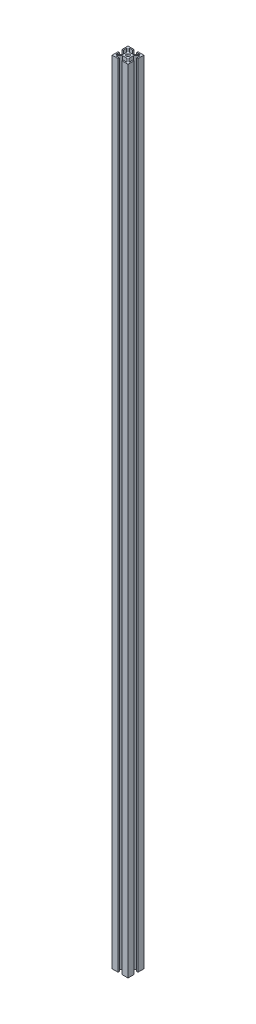
SolidWorks part; units mm, degrees
ref_plane "Front Plane" through (0, 0, 0) normal (0, 0, 1) x (1, 0, 0)
ref_plane "Top Plane" through (0, 0, 0) normal (0, 1, 0) x (1, 0, 0)
ref_plane "Right Plane" through (0, 0, 0) normal (1, 0, 0) x (0, 0, -1)
sketch "Sketch1" plane through (0, 0, 0) normal (0, 1, 0) x (1, 0, 0)
  line L0 (-2.5, -993.4222) -> (-2.5, 49006.5778) construction
  line L1 (-10, 10) -> (-2.5, 10)
  line L2 (-10, 10) -> (-10, 2.5)
  line L3 (-10, -10) -> (-2.5, -10)
  line L4 (10, 10) -> (10, 2.5)
  line L5 (2.5, -994.5334) -> (2.5, 49005.4666) construction
  line L6 (-997.8427, 8.5) -> (49002.1573, 8.5) construction
  line L7 (-999.56, -8.5) -> (49000.44, -8.5) construction
  line L8 (8.5, -999.3828) -> (8.5, 49000.6172) construction
  line L9 (-2.9748, 4) -> (2.9748, 4)
  line L10 (-4, 2.9038) -> (-4, -2.9038)
  line L11 (-2.9748, -4) -> (2.9748, -4)
  line L12 (4, 2.9038) -> (4, -2.9038)
  line L13 (-8.5, -996.7327) -> (-8.5, 49003.2673) construction
  line L14 (2.5, 10) -> (2.5, 8.5)
  line L15 (2.5, 8.5) -> (6.75, 8.5)
  line L16 (8.5, 6.75) -> (8.5, 2.5)
  line L17 (8.5, 2.5) -> (10, 2.5)
  line L18 (-2.5, 10) -> (-2.5, 8.5)
  line L19 (-2.5, 8.5) -> (-6.75, 8.5)
  line L20 (-8.5, 6.75) -> (-8.5, 2.5)
  line L21 (-8.5, 2.5) -> (-10, 2.5)
  line L22 (-2.5, -10) -> (-2.5, -8.5)
  line L23 (-2.5, -8.5) -> (-6.75, -8.5)
  line L24 (-8.5, -6.75) -> (-8.5, -2.5)
  line L25 (-8.5, -2.5) -> (-10, -2.5)
  line L26 (2.5, -10) -> (2.5, -8.5)
  line L27 (2.5, -8.5) -> (6.75, -8.5)
  line L28 (8.5, -6.75) -> (8.5, -2.5)
  line L29 (8.5, -2.5) -> (10, -2.5)
  line L30 (2.5, 10) -> (10, 10)
  line L31 (-10, -2.5) -> (-10, -10)
  line L32 (10, -2.5) -> (10, -10)
  line L33 (0, 0) -> (35355.3391, 35355.3391) construction
  line L34 (2.9748, 4) -> (6.75, 7.7752)
  line L35 (4, 2.9038) -> (7.8462, 6.75)
  line L36 (-1012.3135, 6.75) -> (48987.6865, 6.75) construction
  line L37 (7.8462, 6.75) -> (8.5, 6.75)
  line L38 (6.75, -989.0284) -> (6.75, 49010.9716) construction
  line L39 (6.75, 7.7752) -> (6.75, 8.5)
  line L40 (0, -1000) -> (0, 49000) construction
  line L41 (-1000, 0) -> (49000, 0) construction
  line L42 (-6.75, 7.7752) -> (-6.75, 8.5)
  line L43 (-7.8462, 6.75) -> (-8.5, 6.75)
  line L44 (-2.9748, 4) -> (-6.75, 7.7752)
  line L45 (-4, 2.9038) -> (-7.8462, 6.75)
  line L46 (6.75, -7.7752) -> (6.75, -8.5)
  line L47 (7.8462, -6.75) -> (8.5, -6.75)
  line L48 (4, -2.9038) -> (7.8462, -6.75)
  line L49 (2.9748, -4) -> (6.75, -7.7752)
  line L50 (-2.9748, -4) -> (-6.75, -7.7752)
  line L51 (-6.75, -7.7752) -> (-6.75, -8.5)
  line L52 (-7.8462, -6.75) -> (-8.5, -6.75)
  line L53 (-4, -2.9038) -> (-7.8462, -6.75)
  line L54 (2.5, -10) -> (10, -10)
  circle A0 centre (0, 0) radius 2.15
  dimension "D7" = 4.3
  dimension "D1" = 20
  dimension "D2" = 20
  dimension "D3" = 10
  dimension "D4" = 10
  dimension "D5" = 7.5
  dimension "D6" = 7.5
  dimension "D9" = 4
  dimension "D10" = 4
  dimension "D11" = 1.5
  dimension "D13" = 7.5
  dimension "D15" = 7.5
  dimension "D16" = 1.5
  dimension "D17" = 7.5
  dimension "D18" = 7.5
  dimension "D19" = 1.5
  dimension "D20" = 3.25
  dimension "D21" = 3.25
extrude "Boss-Extrude1" add sketch "Sketch1" along normal blind 1000
